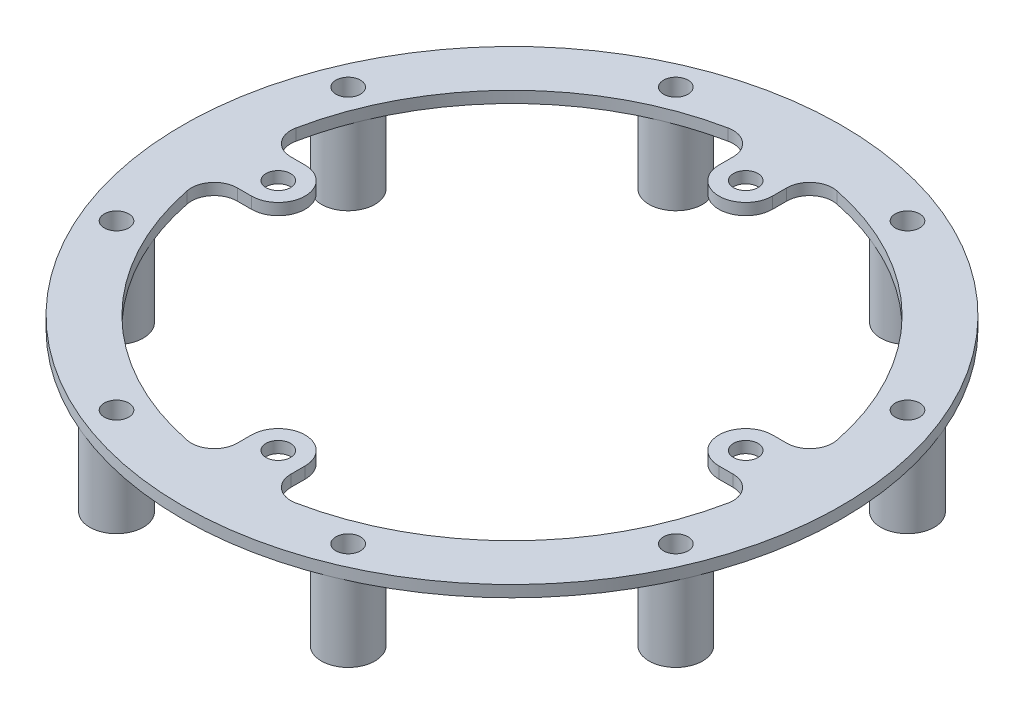
SolidWorks part; units mm, degrees
material "ABS"
ref_plane "Plano frontal" through (0, 0, 0) normal (0, 0, 1) x (1, 0, 0)
ref_plane "Plano superior" through (0, 0, 0) normal (0, 1, 0) x (1, 0, 0)
ref_plane "Plano direito" through (0, 0, 0) normal (1, 0, 0) x (0, 0, -1)
sketch "Esboço1" plane through (0, 0, 0) normal (0, 1, 0) x (1, 0, 0)
  line L0 (-43, 0) -> (43, 0) construction
  line L1 (0, 43) -> (0, -36) construction
  line L2 (0, 0) -> (-39.7268, 16.4554) construction
  line L3 (-3.5, 30.4977) -> (-3.5, 35.8295)
  line L4 (3.5, 30.4977) -> (3.5, 35.8295)
  line L5 (30.4977, 3.5) -> (35.8295, 3.5)
  line L6 (30.4977, -3.5) -> (35.8295, -3.5)
  line L7 (-3.5, -30.4977) -> (-3.5, -35.8295)
  line L8 (3.5, -30.4977) -> (3.5, -35.8295)
  line L9 (-30.4977, 3.5) -> (-35.8295, 3.5)
  line L10 (-30.4977, -3.5) -> (-35.8295, -3.5)
  circle A0 centre (0, 0) radius 43
  arc A1 (-3.5, 35.8295) -> (-35.8295, 3.5) centre (0, 0) ccw
  circle A2 centre (-36.4932, 15.116) radius 1.6
  circle A3 centre (-15.116, 36.4932) radius 1.6
  circle A4 centre (15.116, 36.4932) radius 1.6
  circle A5 centre (36.4932, 15.116) radius 1.6
  circle A6 centre (36.4932, -15.116) radius 1.6
  circle A7 centre (15.116, -36.4932) radius 1.6
  circle A8 centre (-15.116, -36.4932) radius 1.6
  circle A9 centre (-36.4932, -15.116) radius 1.6
  arc A10 (-3.5, 30.4977) -> (3.5, 30.4977) centre (0, 30.4977) ccw
  arc A11 (30.4977, 3.5) -> (30.4977, -3.5) centre (30.4977, 0) ccw
  arc A12 (3.5, -30.4977) -> (-3.5, -30.4977) centre (0, -30.4977) ccw
  arc A13 (-30.4977, -3.5) -> (-30.4977, 3.5) centre (-30.4977, 0) ccw
  arc A14 (35.8295, 3.5) -> (3.5, 35.8295) centre (0, 0) ccw
  arc A15 (3.5, -35.8295) -> (35.8295, -3.5) centre (0, 0) ccw
  arc A16 (-35.8295, -3.5) -> (-3.5, -35.8295) centre (0, 0) ccw
  circle A17 centre (0, 30.4977) radius 1.6
  circle A18 centre (30.4977, 0) radius 1.6
  circle A19 centre (0, -30.4977) radius 1.6
  circle A20 centre (-30.4977, 0) radius 1.6
  point P29 (0, 0)
  point P37 (0, 0)
  point P56 (0, 0)
  dimension "D1" = 86
  dimension "D2" = 7
  dimension "D3" = 22.5
  dimension "D4" = 7
  dimension "D5" = 3.2
  dimension "D10" = 3.2
  dimension "D12" = 1.9
  dimension "D6" = 39.5
  dimension "D8" = 30.4977
  dimension "D7" = 8
  dimension "D9" = 4
  dimension "D11" = 4
extrude "Ressalto-extrusão1" add sketch "Esboço1" along normal mid plane 1.5
fillet "Filete2" radius 3 8 edges at (-3.5, 0, 35.8295) (3.5, 0, 35.8295) (-35.8295, 0, -3.5) (-35.8295, 0, 3.5) (35.8295, 0, -3.5) (35.8295, 0, 3.5) (3.5, 0, -35.8295) (-3.5, 0, -35.8295)
sketch "Esboço2" plane through (0, -0.75, 0) normal (0, -1, 0) x (1, 0, 0)
  circle A0 centre (-15.116, 36.4932) radius 3.5
  circle A1 centre (-15.116, 36.4932) radius 1.6
  circle A2 centre (15.116, 36.4932) radius 3.5
  circle A3 centre (15.116, 36.4932) radius 1.6
  circle A4 centre (36.4932, 15.116) radius 3.5
  circle A5 centre (36.4932, 15.116) radius 1.6
  circle A6 centre (36.4932, -15.116) radius 3.5
  circle A7 centre (36.4932, -15.116) radius 1.6
  circle A8 centre (15.116, -36.4932) radius 3.5
  circle A9 centre (15.116, -36.4932) radius 1.6
  circle A10 centre (-15.116, -36.4932) radius 3.5
  circle A11 centre (-15.116, -36.4932) radius 1.6
  circle A12 centre (-36.4932, -15.116) radius 3.5
  circle A13 centre (-36.4932, -15.116) radius 1.6
  circle A14 centre (-36.4932, 15.116) radius 3.5
  circle A15 centre (-36.4932, 15.116) radius 1.6
  point P28 (0, 0)
  dimension "D1" = 7
  dimension "D2" = 3.2
  dimension "D3" = 8
extrude "Ressalto-extrusão2" add sketch "Esboço2" along normal blind 10
